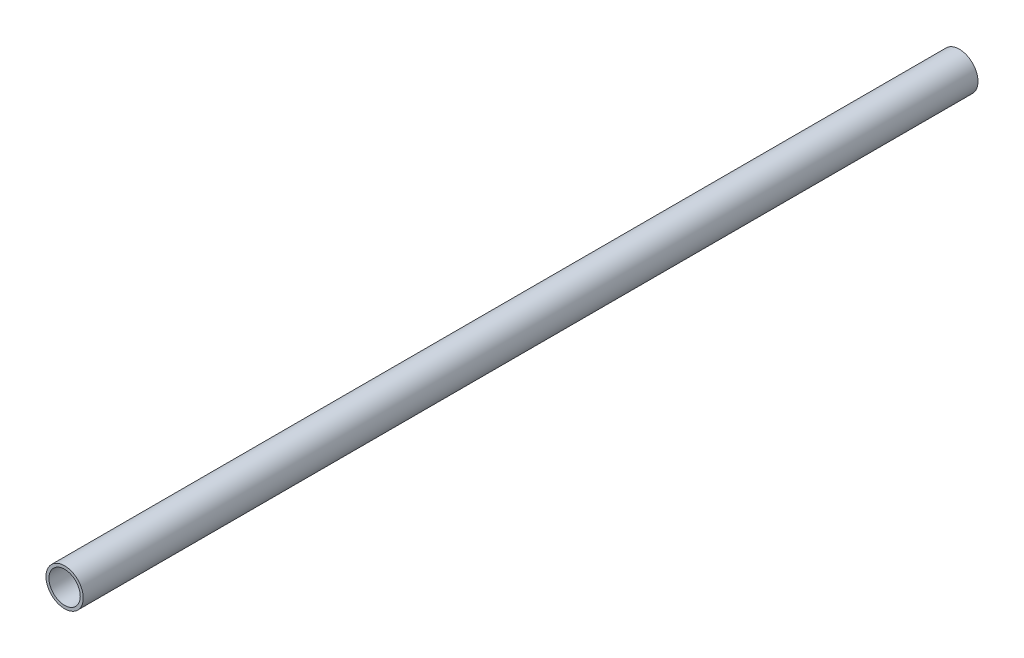
SolidWorks part; units mm, degrees
ref_plane "Front Plane" through (0, 0, 0) normal (0, 0, 1) x (1, 0, 0)
ref_plane "Top Plane" through (0, 0, 0) normal (0, 1, 0) x (1, 0, 0)
ref_plane "Right Plane" through (0, 0, 0) normal (1, 0, 0) x (0, 0, -1)
sketch "Sketch1" plane through (0, 0, 0) normal (0, 0, 1) x (1, 0, 0)
  line L0 (19.05, 0) -> (16.002, 0) construction
  line L1 (-19.05, 0) -> (19.05, 0) construction
  dimension "OD" = 38.1
  dimension "Wall Thickness" = 3.048
sketch "Sketch2" plane through (0, 0, 0) normal (1, 0, 0) x (0, 0, -1)
  line L0 (457.2, 0) -> (-457.2, 0)
  point P4 (0, 0)
  dimension "Length" = 914.4
sketch "Sketch3" plane through (0, 0, 0) normal (0, 0, 1) x (1, 0, 0)
  circle A0 centre (0, 0) radius 19.05
  circle A1 centre (0, 0) radius 16.002
extrude "Boss-Extrude1" add sketch "Sketch3" along normal up to vertex (457.2 mm away) and the other way up to vertex (457.2 mm away) up to point (0, 0, 457.2) other way up to point (0, 0, -457.2)
